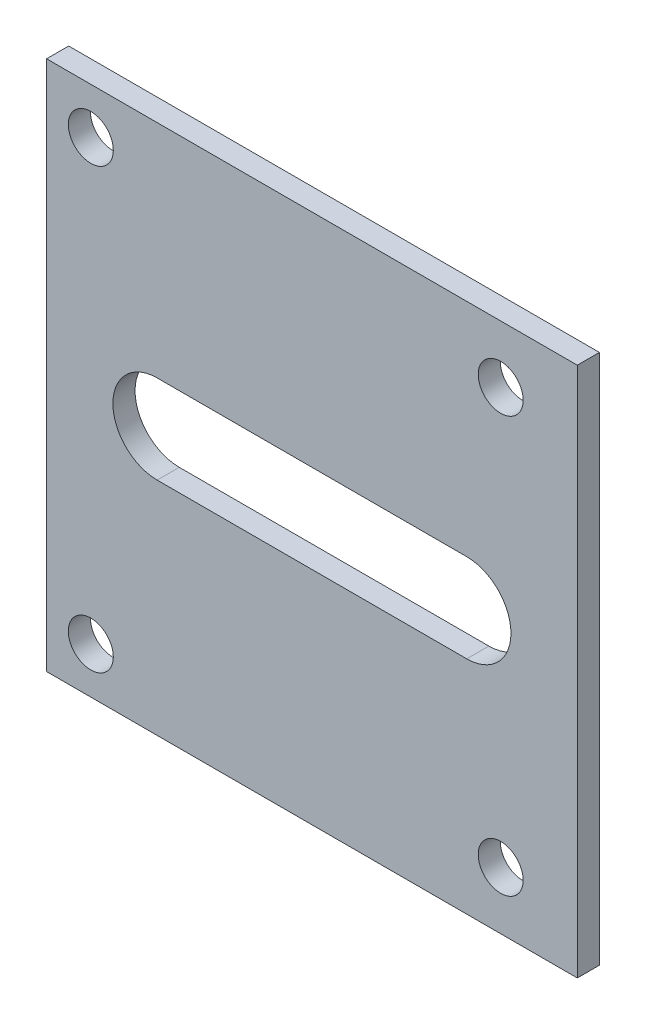
SolidWorks part; units mm, degrees
ref_plane "Front Plane" through (0, 0, 0) normal (0, 0, 1) x (1, 0, 0)
ref_plane "Top Plane" through (0, 0, 0) normal (0, 1, 0) x (1, 0, 0)
ref_plane "Right Plane" through (0, 0, 0) normal (1, 0, 0) x (0, 0, -1)
sketch "Sketch1" plane through (0, 0, 0) normal (0, 0, 1) x (1, 0, 0)
  line L0 (0, 0) -> (76.2, 0)
  line L1 (65.2018, 76.2) -> (65.2018, 0) construction
  line L2 (0, 0) -> (0, 76.2)
  line L3 (0, 76.2) -> (76.2, 76.2)
  line L4 (0, 38.1) -> (71.6609, 38.1) construction
  line L16 (76.2, 76.2) -> (76.2, 0)
  circle A0 centre (6.35, 69.596) radius 3.2291
  circle A1 centre (6.35, 6.604) radius 3.2291
  circle A2 centre (65.2018, 67.945) radius 3.2291
  circle A3 centre (65.2018, 8.255) radius 3.2291
  dimension "D3" = 76.2
  dimension "D6" = 29.845
  dimension "D1" = 76.2
  dimension "D2" = 58.8518
  dimension "D4" = 6.35
  dimension "D5" = 76.2
  dimension "D7" = 6.604
  dimension "D8" = 6.604
extrude "Boss-Extrude3" add sketch "Sketch1" along normal blind 3.175
sketch "Sketch2" plane through (0, 0, 3.175) normal (0, 0, 1) x (1, 0, 0)
  line L0 (0, 38.1) -> (76.2, 38.1) construction
  line L1 (0, 76.2) -> (0, 0) construction
  line L2 (76.2, 0) -> (76.2, 76.2) construction
  line L3 (38.1, 76.2) -> (38.1, 0) construction
  line L4 (76.2, 76.2) -> (0, 76.2) construction
  line L5 (0, 0) -> (76.2, 0) construction
  line L6 (15.875, 38.1) -> (60.325, 38.1) construction
  line L7 (15.875, 44.45) -> (60.325, 44.45)
  line L8 (15.875, 31.75) -> (60.325, 31.75)
  arc A0 (15.875, 44.45) -> (15.875, 31.75) centre (15.875, 38.1) ccw
  arc A1 (60.325, 31.75) -> (60.325, 44.45) centre (60.325, 38.1) ccw
  point P14 (38.1, 38.1)
extrude "Cut-Extrude1" cut sketch "Sketch2" against normal blind 3.175
